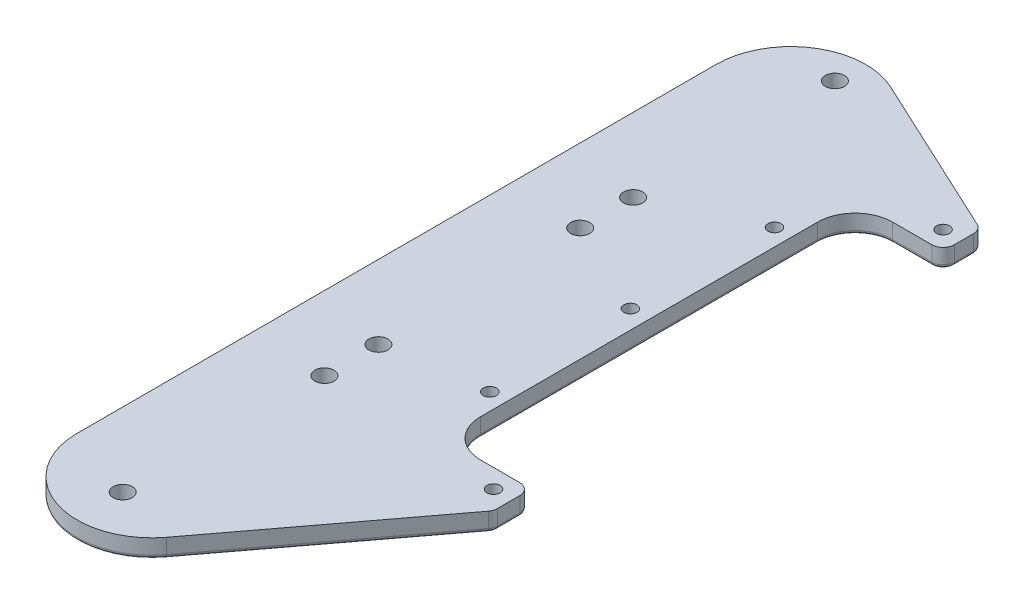
SolidWorks part; units mm, degrees
ref_plane "Front Plane" through (0, 0, 0) normal (0, 0, 1) x (1, 0, 0)
ref_plane "Top Plane" through (0, 0, 0) normal (0, 1, 0) x (1, 0, 0)
ref_plane "Right Plane" through (0, 0, 0) normal (1, 0, 0) x (0, 0, -1)
sketch "Sketch1" plane through (0, 0, 0) normal (0, 1, 0) x (1, 0, 0)
  line L0 (28.48, -65) -> (28.48, -55)
  line L1 (28.48, -55) -> (5, -55)
  line L2 (5, -55) -> (5, 55)
  line L3 (5, 55) -> (28.48, 55)
  line L4 (28.48, 55) -> (28.48, 65)
  line L5 (28.48, 65) -> (-45, 99.2643)
  line L6 (-45, 99.2643) -> (-45, -162.5113)
  line L7 (-45, -162.5113) -> (28.48, -65)
  line L8 (0, 0) -> (5, 0) construction
  line L9 (23.48, -60) -> (23.48, -55) construction
  line L10 (23.48, 60) -> (28.48, 60) construction
  circle A0 centre (0, 0) radius 1.75
  circle A1 centre (0.48, 0) radius 1.75 construction
  circle A2 centre (0.48, -38) radius 1.75
  circle A3 centre (0.48, -38) radius 1.75 construction
  circle A4 centre (23.48, -60) radius 1.75
  circle A5 centre (23.48, -60) radius 1.75 construction
  circle A6 centre (0.48, 38) radius 1.75
  circle A7 centre (0.48, 38) radius 1.75 construction
  circle A8 centre (23.48, 60) radius 1.75
  circle A9 centre (23.48, 60) radius 1.75 construction
  circle A10 centre (23.48, 60) radius 1.75 construction
  point P30 (5, 0)
  point P33 (28.48, 60)
  dimension "D1" = 115
  dimension "D2" = 5
  dimension "D3" = 143
  dimension "D4" = 50
extrude "Boss-Extrude1" add sketch "Sketch1" along normal blind 5
fillet "Fillet3" radius 10 2 edges at (5, 2.5, 55) (5, 2.5, -55)
fillet "Fillet4" radius 3 4 edges at (28.48, 2.5, -65) (28.48, 2.5, 65) (28.48, 2.5, 55) (28.48, 2.5, -55)
fillet "Fillet5" radius 20 2 edges at (-45, 2.5, 162.5113) (-45, 2.5, -99.2643)
sketch "Sketch2" plane through (0, 0, 0) normal (0, -1, 0) x (1, 0, 0)
  circle A0 centre (-25.3273, 41.9336) radius 4
  circle A1 centre (-25.3273, -11.9336) radius 4
  circle A2 centre (-25.3273, -26.0664) radius 4
  circle A3 centre (-25.3273, -79.9336) radius 4
  circle A8 centre (-25.3273, 56.3434) radius 4
  circle A9 centre (-25.3273, 110.2107) radius 4
  circle A12 centre (-25.3273, -79.9336) radius 3.29 construction
  circle A13 centre (-25.3273, -26.0664) radius 3.29 construction
  circle A14 centre (-25.3273, -11.9336) radius 3.29 construction
  circle A15 centre (-25.3273, 41.9336) radius 3.29 construction
  circle A16 centre (-25.3273, 56.3434) radius 3.29 construction
  circle A17 centre (-25.3273, 110.2107) radius 3.29 construction
  dimension "D1" = 8
extrude "Boss-Extrude2" add sketch "Sketch2" along normal up to surface (5 mm away)
sketch "Sketch3" plane through (0, 5, 0) normal (0, 1, 0) x (1, 0, 0)
  circle A0 centre (-25.3273, 79.9336) radius 2.55
  circle A1 centre (-25.3273, 26.0664) radius 2.55
  circle A2 centre (-25.3273, 11.9336) radius 2.55
  circle A3 centre (-25.3273, -41.9336) radius 2.55
  circle A4 centre (-25.3273, 79.9336) radius 4 construction
  circle A5 centre (-25.3273, 26.0664) radius 4 construction
  circle A6 centre (-25.3273, -41.9336) radius 4 construction
  circle A7 centre (-25.3273, 11.9336) radius 4 construction
  circle A8 centre (-25.3273, -56.3434) radius 2.55
  circle A9 centre (-25.3273, -110.2107) radius 2.55
  circle A10 centre (-25.3273, -110.2107) radius 4 construction
  circle A11 centre (-25.3273, -56.3434) radius 4 construction
  dimension "D1" = 5.1
extrude "Cut-Extrude1" cut sketch "Sketch3" against normal offset from surface (7 mm away) 3 up to face at (-25.3273, -5, -75.9336)
sketch "Sketch4" plane through (0, -5, 0) normal (0, -1, 0) x (1, 0, 0)
  circle A0 centre (-25.3273, -79.9336) radius 1.55
  circle A1 centre (-25.3273, -26.0664) radius 1.55
  circle A2 centre (-25.3273, -11.9336) radius 1.55
  circle A3 centre (-25.3273, 41.9336) radius 1.55
  circle A4 centre (-25.3273, 41.9336) radius 4 construction
  circle A5 centre (-25.3273, -11.9336) radius 4 construction
  circle A6 centre (-25.3273, -26.0664) radius 4 construction
  circle A7 centre (-25.3273, -79.9336) radius 4 construction
  circle A8 centre (-25.3273, 56.3434) radius 1.55
  circle A9 centre (-25.3273, 110.2107) radius 1.55
  circle A10 centre (-25.3273, 110.2107) radius 4 construction
  circle A11 centre (-25.3273, 56.3434) radius 4 construction
  dimension "D1" = 3.1
extrude "Cut-Extrude2" cut sketch "Sketch4" against normal through all both and the other way through all
fillet "Fillet6" radius 2 12 edges at (-25.3273, 0, -75.9336) (-25.3273, 0, -22.0664) (-25.3273, 0, -7.9336) (-25.3273, 0, 45.9336) (-25.3273, -5, 45.9336) (-25.3273, -5, -7.9336) (-25.3273, -5, -22.0664) (-25.3273, -5, -75.9336) (-25.3273, 0, 114.2107) (-25.3273, -5, 114.2107) (-25.3273, 0, 60.3434) (-25.3273, -5, 60.3434)
fillet "Fillet7" radius 1 16 edges at (20.24, 0, -55) (27.6013, 0, -55.8787) (28.48, 0, -60.5444) (28.0102, 0, -64.7007) (5.1001, 0, -75.9022) (-35.746, 0, -84.7384) (-45, 0, 17.4335) (-31.3461, 0, 121.704) (9.4243, 0, 90.2878) (28.325, 0, 64.9481) (28.48, 0, 60.9981) (27.6013, 0, 55.8787) (20.24, 0, 55) (7.9289, 0, 52.0711) (5, 0, 0) (7.9289, 0, -52.0711)
sketch "Sketch6" plane through (0, 0, 0) normal (0, -1, 0) x (-1, 0, 0)
  line L0 (40, 56) -> (-15, 56) construction
  line L1 (44, -102.7376) -> (44, 67.8706) construction
  arc A0 (-4, 45) -> (-15, 56) centre (-15, 45) ccw construction
  text T0 "^UP\r\nDC-DC Mount V2\r\nhitchco-mk4"
  dimension "D1" = 55
extrude "Cut-Extrude3" cut sketch "Sketch6" against normal blind 1
